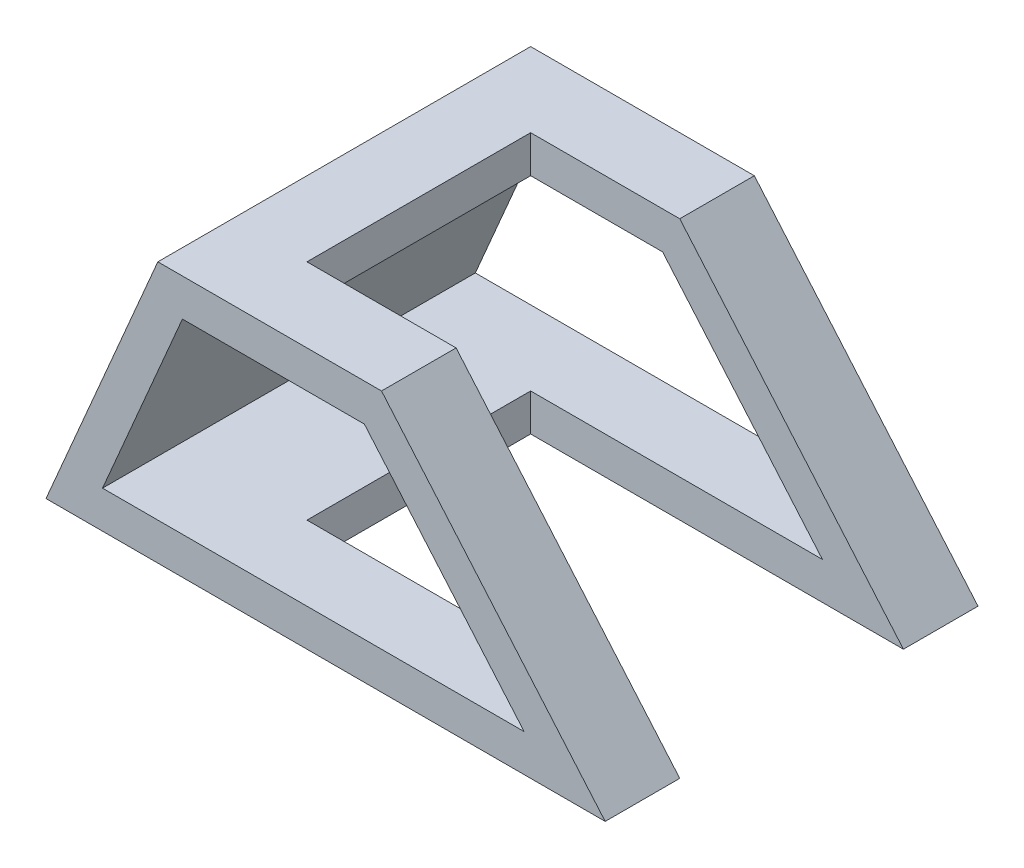
SolidWorks part; units mm, degrees
ref_plane "Front Plane" through (0, 0, 0) normal (0, 0, 1) x (1, 0, 0)
ref_plane "Top Plane" through (0, 0, 0) normal (0, 1, 0) x (1, 0, 0)
ref_plane "Right Plane" through (0, 0, 0) normal (1, 0, 0) x (0, 0, -1)
sketch "Sketch1" plane through (0, 0, 0) normal (0, 0, 1) x (1, 0, 0)
  line L0 (0, 0) -> (150, 0)
  line L1 (150, 0) -> (90, 70)
  line L2 (90, 70) -> (30, 70)
  line L3 (30, 70) -> (0, 0)
  line L4 (36.594, 60) -> (15.1654, 10)
  line L5 (15.1654, 10) -> (128.2578, 10)
  line L6 (128.2578, 10) -> (85.4007, 60)
  line L7 (85.4007, 60) -> (36.594, 60)
  dimension "D1" = 150
  dimension "D2" = 70
  dimension "D3" = 30
  dimension "D4" = 60
  dimension "D5" = 10
extrude "Boss-Extrude1" add sketch "Sketch1" along normal blind 100
sketch "Sketch2" plane through (0, 70, 0) normal (0, 1, 0) x (1, 0, 0)
  line L0 (150, -100) -> (150, 0) construction
  line L1 (150, -20) -> (50, -20)
  line L2 (150, -20) -> (150, -80)
  line L3 (150, -80) -> (50, -80)
  line L4 (50, -20) -> (50, -80)
  line L5 (150, 0) -> (90, 0) construction
  line L6 (150, -100) -> (90, -100) construction
  dimension "D1" = 100
  dimension "D2" = 20
  dimension "D3" = 20
extrude "Cut-Extrude1" cut sketch "Sketch2" against normal through all
